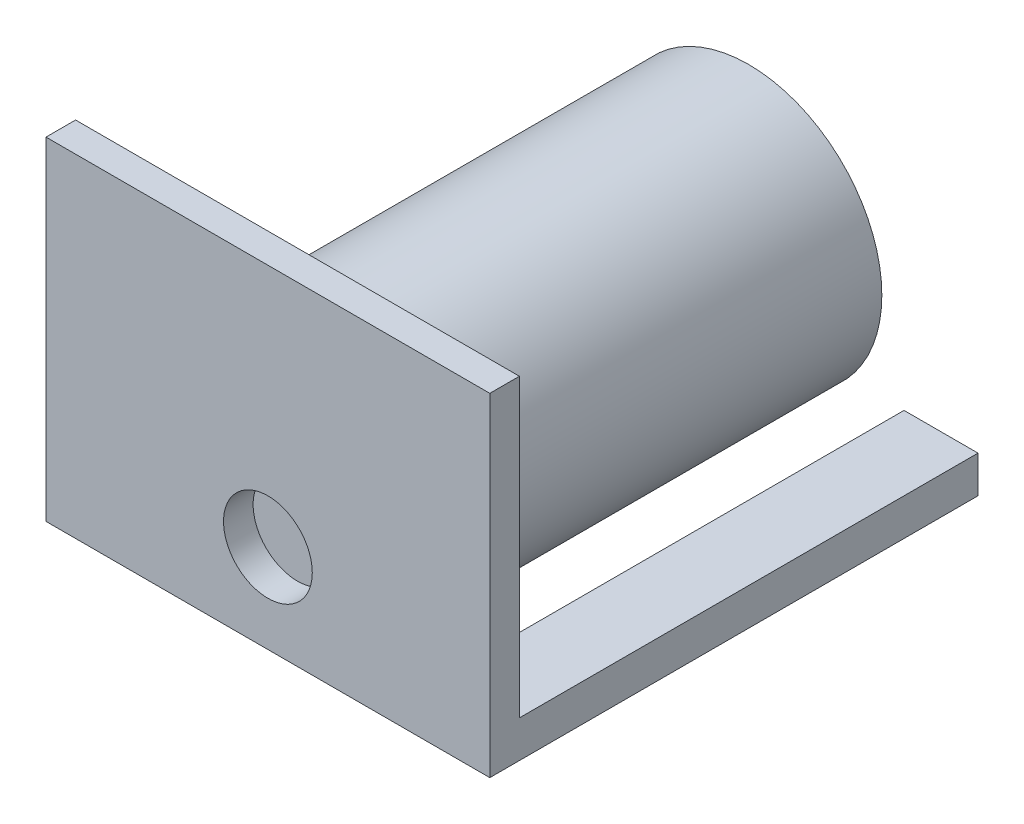
SolidWorks part; units mm, degrees
ref_plane "Front Plane" through (0, 0, 0) normal (0, 0, 1) x (1, 0, 0)
ref_plane "Top Plane" through (0, 0, 0) normal (0, 1, 0) x (1, 0, 0)
ref_plane "Right Plane" through (0, 0, 0) normal (1, 0, 0) x (0, 0, -1)
sketch "Sketch1" plane through (0, 0, 0) normal (0, 0, 1) x (1, 0, 0)
  line L1 (-29.306, 22.7583) -> (30.694, 22.7583)
  line L2 (-29.306, 22.7583) -> (-29.306, -22.2417)
  line L3 (-29.306, -22.2417) -> (30.694, -22.2417)
  line L4 (30.694, 22.7583) -> (30.694, -22.2417)
extrude "Boss-Extrude1" add sketch "Sketch1" along normal blind 4
sketch "Sketch2" plane through (0, 0, 0) normal (0, 0, -1) x (-1, 0, 0)
  line L2 (-30.694, -22.2417) -> (-20.694, -22.2417)
  line L3 (-30.694, -22.2417) -> (-30.694, -17.2417)
  line L4 (-30.694, -17.2417) -> (-20.694, -17.2417)
  line L5 (-20.694, -22.2417) -> (-20.694, -17.2417)
  line L6 (29.306, -22.2417) -> (19.306, -22.2417)
  line L7 (29.306, -22.2417) -> (29.306, -17.2417)
  line L8 (29.306, -17.2417) -> (19.306, -17.2417)
  line L9 (19.306, -22.2417) -> (19.306, -17.2417)
extrude "Boss-Extrude3" add sketch "Sketch2" along normal blind 62
sketch "Sketch3" plane through (0, 0, 0) normal (0, 0, -1) x (-1, 0, 0)
  line L2 (19.306, -22.2417) -> (-20.694, -22.2417) construction
  line L3 (-0.694, -22.2417) -> (-0.694, -4.2417) construction
  circle A0 centre (-0.694, -4.2417) radius 18
extrude "Boss-Extrude4" add sketch "Sketch3" along normal blind 61
sketch "Sketch4" plane through (0, 0, 4) normal (0, 0, 1) x (1, 0, 0)
  line L2 (0.694, -22.2417) -> (0.694, -10.2417)
  circle A0 centre (0.694, -10.2417) radius 6
extrude "Cut-Extrude1" cut sketch "Sketch4" against normal blind 4
scale "Scale1" bodies to scale 105 scale about centroid uniform scaling yes scale factor 0.15
